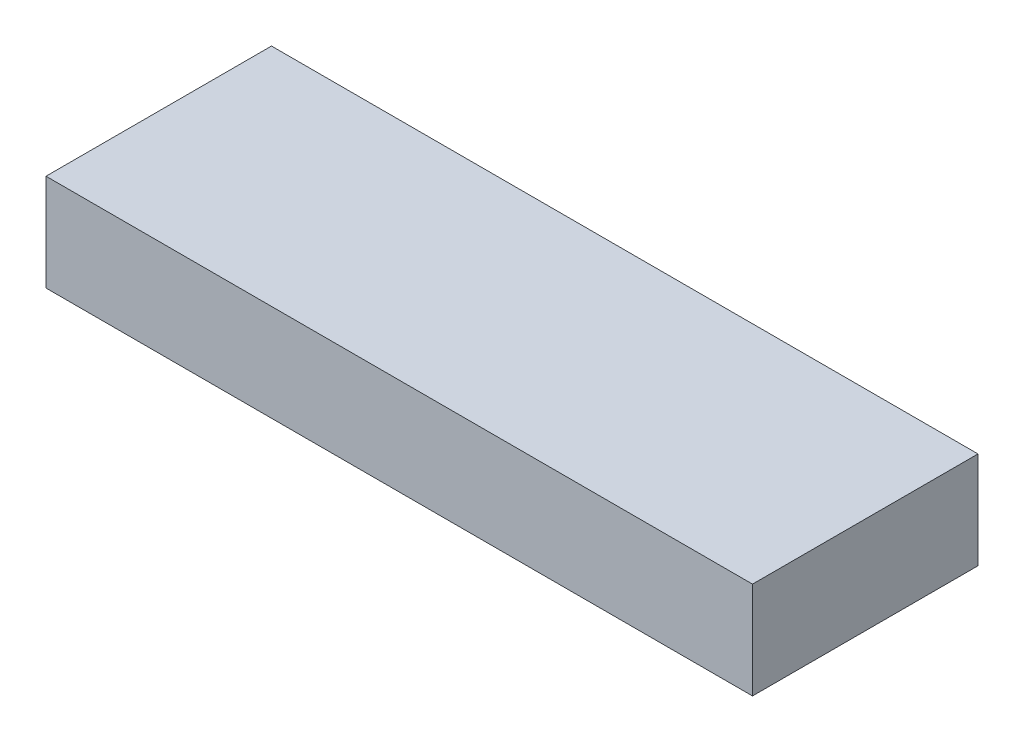
SolidWorks part; units mm, degrees
ref_plane "Front Plane" through (0, 0, 0) normal (0, 0, 1) x (1, 0, 0)
ref_plane "Top Plane" through (0, 0, 0) normal (0, 1, 0) x (1, 0, 0)
ref_plane "Right Plane" through (0, 0, 0) normal (1, 0, 0) x (0, 0, -1)
sketch "Sketch1" plane through (0, 0, 0) normal (0, 1, 0) x (1, 0, 0)
  line L1 (0, 0) -> (106.3244, 0)
  line L2 (0, 0) -> (0, 33.9344)
  line L3 (0, 33.9344) -> (106.3244, 33.9344)
  line L4 (106.3244, 0) -> (106.3244, 33.9344)
  dimension "D1" = 106.3244
  dimension "D2" = 33.9344
extrude "Boss-Extrude1" add sketch "Sketch1" along normal blind 14.5796
